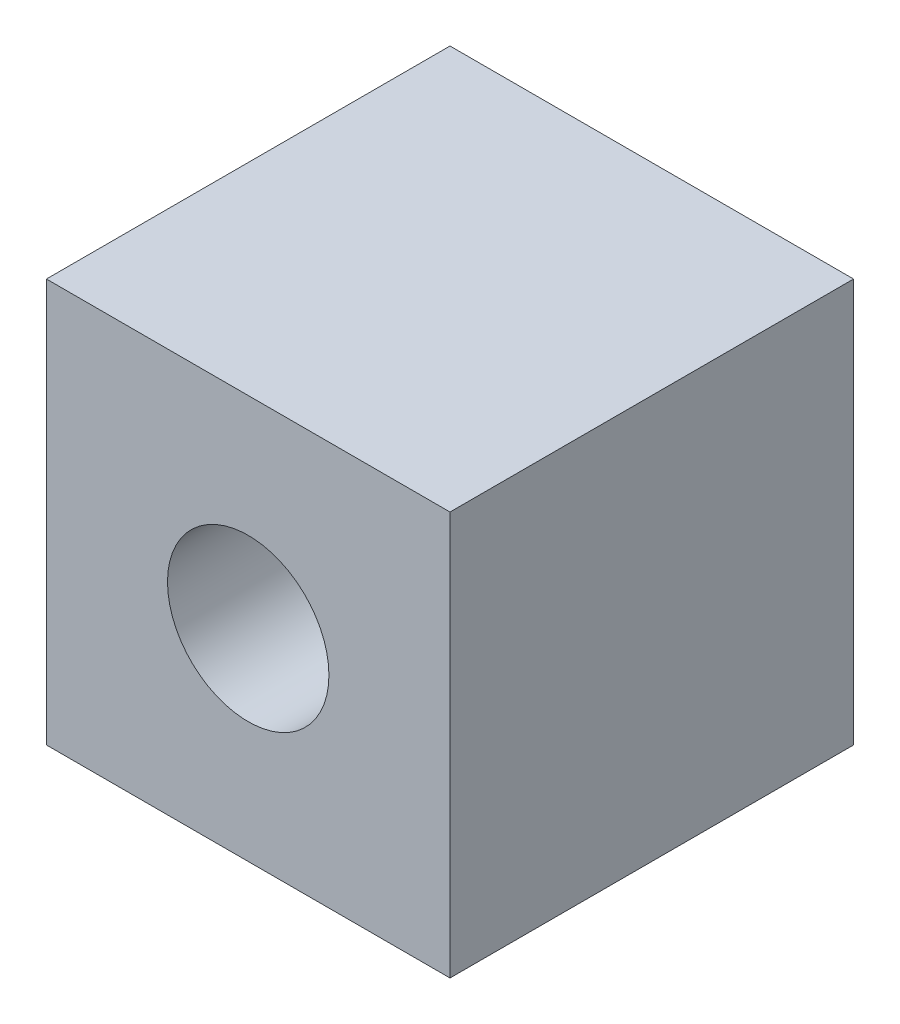
SolidWorks part; units mm, degrees
ref_plane "Front Plane" through (0, 0, 0) normal (0, 0, 1) x (1, 0, 0)
ref_plane "Top Plane" through (0, 0, 0) normal (0, 1, 0) x (1, 0, 0)
ref_plane "Right Plane" through (0, 0, 0) normal (1, 0, 0) x (0, 0, -1)
sketch "Sketch1" plane through (0, 0, 0) normal (0, 0, 1) x (1, 0, 0)
  line L1 (0, 0) -> (10, 0)
  line L2 (0, 0) -> (0, 10)
  line L3 (0, 10) -> (10, 10)
  line L4 (10, 0) -> (10, 10)
extrude "Boss-Extrude1" add sketch "Sketch1" along normal blind 10
sketch "Sketch2" plane through (0, 0, 0) normal (0, 0, 1) x (1, 0, 0)
  circle A0 centre (5, 5) radius 2
extrude "Cut-Extrude1" cut sketch "Sketch2" along normal through all
